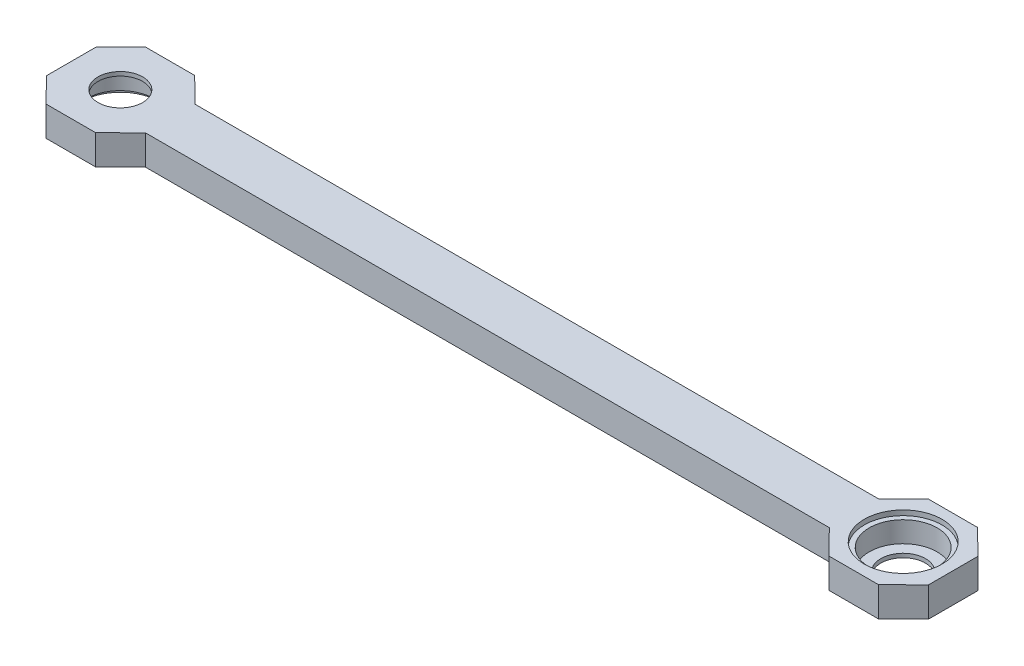
SolidWorks part; units mm, degrees
ref_plane "前视基准面" through (0, 0, 0) normal (0, 0, 1) x (1, 0, 0)
ref_plane "上视基准面" through (0, 0, 0) normal (0, 1, 0) x (1, 0, 0)
ref_plane "右视基准面" through (0, 0, 0) normal (1, 0, 0) x (0, 0, -1)
sketch "草图1" plane through (0, 0, 0) normal (0, 1, 0) x (1, 0, 0)
  line L0 (-56.1468, 0) -> (96.1142, 0) construction
  line L9 (-65.2623, 5) -> (-70.3633, 10)
  line L10 (-70.3633, 10) -> (-80.3633, 10)
  line L19 (-80.3633, 10) -> (-85.2623, 5)
  line L20 (-85.2623, 5) -> (-85.2623, -5)
  line L23 (72.7377, 5) -> (77.6367, 10)
  line L24 (77.6367, 10) -> (87.6367, 10)
  line L25 (87.6367, 10) -> (92.7398, 5)
  line L26 (92.7398, 5) -> (92.7398, -5)
  line L27 (-75.3633, 10) -> (-75.3633, -5.1974) construction
  line L28 (82.6367, 10) -> (82.6367, -7.8958) construction
  line L29 (-65.2623, -5) -> (-70.3633, -10)
  line L30 (-70.3633, -10) -> (-80.3633, -10)
  line L31 (-80.3633, -10) -> (-85.2623, -5)
  line L32 (87.6367, -10) -> (92.7398, -5)
  line L33 (77.6367, -10) -> (87.6367, -10)
  line L34 (72.7377, -5) -> (77.6367, -10)
  line L35 (-65.2623, 5) -> (72.7377, 5)
  line L36 (72.7377, -5) -> (-65.2623, -5)
  circle A0 centre (-75.3633, 0) radius 4.5
  circle A2 centre (82.6367, 0) radius 4.5
  point P18 (-27.2623, 0)
  point P24 (-85.2623, 0)
  point P25 (92.7398, 0)
  point P28 (72.7377, 0)
  dimension "D1" = 158
  dimension "D2" = 10
  dimension "D11" = 9
  dimension "D12" = 9
  dimension "D3" = 5
  dimension "D4" = 20.0021
  dimension "D5" = 10
  dimension "D6" = 7
  dimension "D7" = 10
  dimension "D8" = 7
  dimension "D9" = 10
  dimension "D10" = 5
  dimension "D13" = 20
extrude "凸台-拉伸1" add sketch "草图1" along normal blind 6
sketch "草图2" plane through (0, 6, 0) normal (0, 1, 0) x (1, 0, 0)
  circle A0 centre (82.6367, 0) radius 6.85
  dimension "D1" = 13.7
extrude "切除-拉伸1" cut sketch "草图2" against normal blind 5.2
sketch "草图3" plane through (0, 6, 0) normal (0, 1, 0) x (1, 0, 0)
  circle A0 centre (82.6367, 0) radius 7.85
  dimension "D1" = 15.7
extrude "切除-拉伸2" cut sketch "草图3" against normal blind 1
sketch "草图5" plane through (0, 0, 0) normal (0, -1, 0) x (1, 0, 0)
  circle A0 centre (-75.3633, 0) radius 6.85
  dimension "D1" = 13.7
extrude "切除-拉伸3" cut sketch "草图5" against normal blind 5.2
sketch "草图6" plane through (0, 0, 0) normal (0, -1, 0) x (1, 0, 0)
  circle A0 centre (-75.3633, 0) radius 7.85
  dimension "D1" = 15.7
extrude "切除-拉伸4" cut sketch "草图6" against normal blind 1
